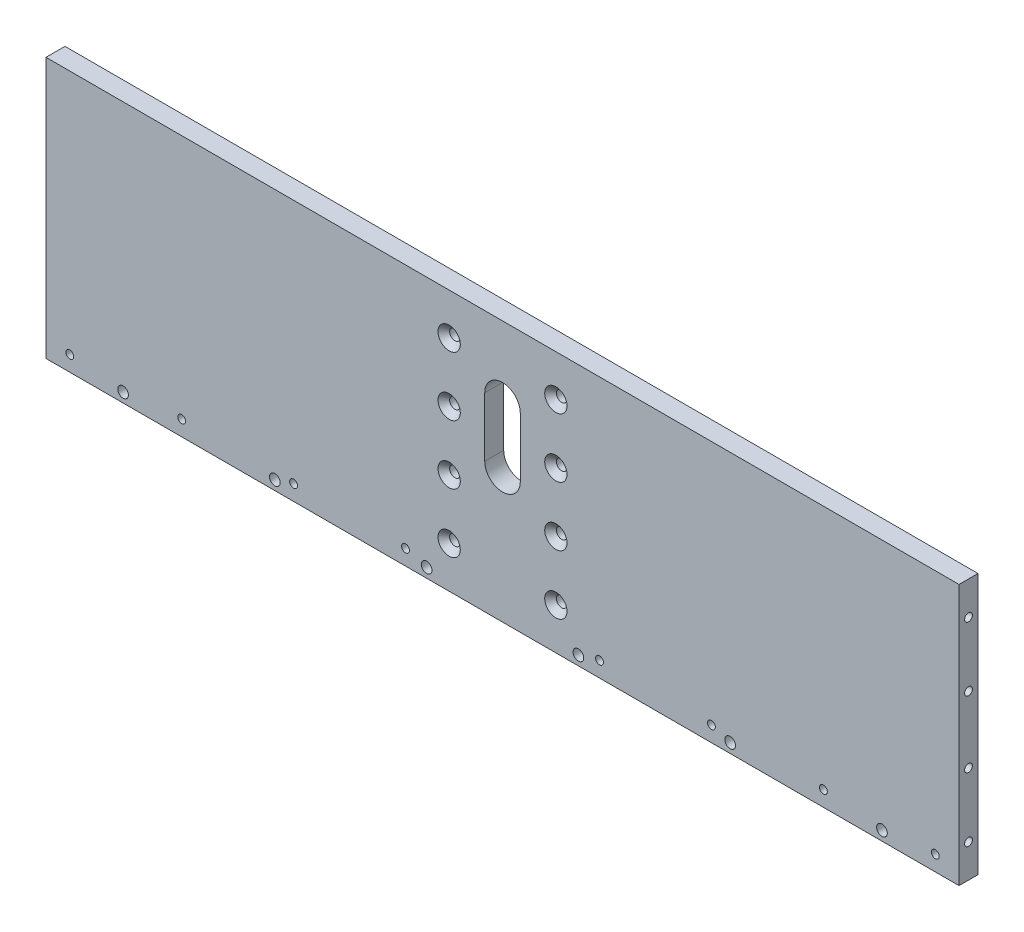
SolidWorks part; units mm, degrees
material "7079 Alloy"
ref_plane "Front Plane" through (0, 0, 0) normal (0, 0, 1) x (1, 0, 0)
ref_plane "Top Plane" through (0, 0, 0) normal (0, 1, 0) x (1, 0, 0)
ref_plane "Right Plane" through (0, 0, 0) normal (1, 0, 0) x (0, 0, -1)
sketch "Sketch1" plane through (0, 0, 0) normal (0, 0, 1) x (1, 0, 0)
  line L0 (-192.5, 0) -> (0, 0) construction
  line L1 (-192.5, -55) -> (192.5, -55)
  line L2 (-192.5, -55) -> (-192.5, 55)
  line L3 (-192.5, 55) -> (192.5, 55)
  line L4 (192.5, -55) -> (192.5, 55)
  line L5 (0, 0) -> (0, 55) construction
  dimension "D1" = 110
  dimension "D2" = 385
extrude "Extrude1" add sketch "Sketch1" along normal blind 8
sketch "Sketch2" plane through (0, 0, 8) normal (0, 0, 1) x (1, 0, 0)
  line L0 (0, 0) -> (0, 55) construction
  line L1 (192.5, 55) -> (-192.5, 55) construction
  line L2 (22.5, 55) -> (22.5, 49.9279) construction
  line L3 (22.5, 49.9279) -> (22.5, -49.9279) construction
  line L4 (22.5, -49.9279) -> (22.5, -55) construction
  line L5 (-192.5, -55) -> (192.5, -55) construction
  line L6 (192.5, -55) -> (192.5, 55) construction
  line L7 (22.5, 0) -> (192.5, 0) construction
  circle A0 centre (22.5, 37.5) radius 2
  circle A1 centre (22.5, 12.5) radius 2
  circle A2 centre (22.5, -12.5) radius 2
  circle A3 centre (-22.5, -12.5) radius 2
  circle A4 centre (-22.5, -37.5) radius 2
  circle A5 centre (22.5, -37.5) radius 2
  circle A6 centre (-22.5, 12.5) radius 2
  circle A7 centre (-22.5, 37.5) radius 2
  dimension "D6" = 4
  dimension "D1" = 37.5
  dimension "D2" = 45
  dimension "D5" = 25
extrude "Cut-Extrude1" cut sketch "Sketch2" against normal blind 10
hole_wizard "CSK for M4 Flat Head Machine Screw1" positions "Sketch4" profile "Sketch3" countersink size "M4" standard "Ansi Metric" end condition through all
sketch "Sketch4" plane through (0, 0, 8) normal (0, 0, 1) x (1, 0, 0)
  point P1 (22.5, 37.5)
  point P4 (22.5, 12.5)
  point P19 (-22.5, 12.5)
  point P25 (-22.5, 37.5)
  point P28 (22.5, -12.5)
  point P31 (-22.5, -12.5)
  point P34 (-22.5, -37.5)
  point P37 (22.5, -37.5)
sketch "Sketch3" plane through (22.5, 37.5, 8) normal (1, 0, 0) x (0, -1, 0)
  line L0 (0, 0) -> (0, 8)
  line L1 (0, 8) -> (2.25, 8)
  line L2 (2.25, 8) -> (2.25, 2.45)
  line L3 (2.25, 2.45) -> (4.7, 0)
  line L5 (4.7, 0) -> (0, 0)
  line L6 (-2.25, 2.45) -> (-4.7, 0) construction
  line L11 (0, -6.35) -> (0, 107.95) construction
  dimension "Thru Hole Dia." = 4.5
  dimension "Thru Hole Depth" = 8
  dimension "Near C'Sink Dia." = 9.4
  dimension "Near C'Sink Angle" = 90
sketch "Sketch5" plane through (192.5, 0, 0) normal (1, 0, 0) x (0, 0, -1)
  line L0 (-4, 55) -> (-4, -55) construction
  line L1 (-8, 55) -> (0, 55) construction
  line L2 (-8, -55) -> (0, -55) construction
  line L3 (0, 0) -> (-8, 0) construction
  line L4 (0, -55) -> (0, 55) construction
  line L5 (-8, -55) -> (-8, 55) construction
  circle A0 centre (-4, 41) radius 1.65
  circle A1 centre (-4, 14) radius 1.65
  circle A2 centre (-4, -41) radius 1.65
  circle A3 centre (-4, -14) radius 1.65
  dimension "D1" = 3.3
  dimension "D3" = 27
  dimension "D2" = 14
extrude "Cut-Extrude2" cut sketch "Sketch5" against normal blind 15
mirror "Mirror1" about plane through (0, 0, 0) normal (1, 0, 0) of "Cut-Extrude2"
sketch "Sketch6" plane through (0, 0, 0) normal (0, 0, -1) x (-1, 0, 0)
  line L0 (192.5, -55) -> (-192.5, -55) construction
  line L2 (0, -51) -> (-192.5, -51) construction
  line L3 (-192.5, -55) -> (-192.5, 55) construction
  circle A0 centre (-96, -51) radius 2.25
  circle A1 centre (-32, -51) radius 2.25
  circle A2 centre (32, -51) radius 2.25
  circle A3 centre (96, -51) radius 2.25
  circle A4 centre (-160, -51) radius 2.25
  circle A5 centre (160, -51) radius 2.25
  dimension "D2" = 6
  dimension "D4" = 4
  dimension "D5" = 4.5
  dimension "D3" = 64
  dimension "D1" = 32.5
extrude "Cut-Extrude3" cut sketch "Sketch6" against normal blind 10
sketch "Sketch9" plane through (0, 0, 0) normal (0, 0, -1) x (-1, 0, 0)
  line L0 (-167.5, 40) -> (-167.5, -40) construction
  line L1 (-162.5, 40) -> (-162.5, -40)
  line L2 (-172.5, 40) -> (-172.5, -40)
  line L3 (-192.5, -55) -> (-192.5, 55) construction
  line L4 (-192.5, 55) -> (192.5, 55) construction
  line L5 (-154.5, 40) -> (-154.5, -40) construction
  line L6 (-149.5, 40) -> (-149.5, -40)
  line L7 (-159.5, 40) -> (-159.5, -40)
  line L8 (-141.5, 40) -> (-141.5, -40) construction
  line L9 (-136.5, 40) -> (-136.5, -40)
  line L10 (-146.5, 40) -> (-146.5, -40)
  line L11 (-128.5, 40) -> (-128.5, -40) construction
  line L12 (-123.5, 40) -> (-123.5, -40)
  line L13 (-133.5, 40) -> (-133.5, -40)
  line L14 (-115.5, 40) -> (-115.5, -40) construction
  line L15 (-110.5, 40) -> (-110.5, -40)
  line L16 (-120.5, 40) -> (-120.5, -40)
  line L17 (-102.5, 40) -> (-102.5, -40) construction
  line L18 (-97.5, 40) -> (-97.5, -40)
  line L19 (-107.5, 40) -> (-107.5, -40)
  line L20 (-89.5, 40) -> (-89.5, -40) construction
  line L21 (-84.5, 40) -> (-84.5, -40)
  line L22 (-94.5, 40) -> (-94.5, -40)
  line L23 (-76.5, 40) -> (-76.5, -40) construction
  line L24 (-71.5, 40) -> (-71.5, -40)
  line L25 (-81.5, 40) -> (-81.5, -40)
  line L26 (-63.5, 40) -> (-63.5, -40) construction
  line L27 (-58.5, 40) -> (-58.5, -40)
  line L28 (-68.5, 40) -> (-68.5, -40)
  line L29 (-50.5, 40) -> (-50.5, -40) construction
  line L30 (-45.5, 40) -> (-45.5, -40)
  line L31 (-55.5, 40) -> (-55.5, -40)
  line L32 (-37.5, 40) -> (-37.5, -40) construction
  line L33 (-32.5, 40) -> (-32.5, -40)
  line L34 (-42.5, 40) -> (-42.5, -40)
  line L35 (0, 55) -> (0, -55) construction
  line L36 (192.5, -55) -> (-192.5, -55) construction
  line L37 (167.5, 40) -> (167.5, -40) construction
  line L38 (162.5, 40) -> (162.5, -40)
  line L39 (172.5, 40) -> (172.5, -40)
  line L40 (154.5, 40) -> (154.5, -40) construction
  line L41 (149.5, 40) -> (149.5, -40)
  line L42 (159.5, 40) -> (159.5, -40)
  line L43 (141.5, 40) -> (141.5, -40) construction
  line L44 (136.5, 40) -> (136.5, -40)
  line L45 (146.5, 40) -> (146.5, -40)
  line L46 (128.5, 40) -> (128.5, -40) construction
  line L47 (123.5, 40) -> (123.5, -40)
  line L48 (133.5, 40) -> (133.5, -40)
  line L49 (115.5, 40) -> (115.5, -40) construction
  line L50 (110.5, 40) -> (110.5, -40)
  line L51 (120.5, 40) -> (120.5, -40)
  line L52 (102.5, 40) -> (102.5, -40) construction
  line L53 (97.5, 40) -> (97.5, -40)
  line L54 (107.5, 40) -> (107.5, -40)
  line L55 (89.5, 40) -> (89.5, -40) construction
  line L56 (84.5, 40) -> (84.5, -40)
  line L57 (94.5, 40) -> (94.5, -40)
  line L58 (76.5, 40) -> (76.5, -40) construction
  line L59 (71.5, 40) -> (71.5, -40)
  line L60 (81.5, 40) -> (81.5, -40)
  line L61 (63.5, 40) -> (63.5, -40) construction
  line L62 (58.5, 40) -> (58.5, -40)
  line L63 (68.5, 40) -> (68.5, -40)
  line L64 (50.5, 40) -> (50.5, -40) construction
  line L65 (45.5, 40) -> (45.5, -40)
  line L66 (55.5, 40) -> (55.5, -40)
  line L67 (37.5, 40) -> (37.5, -40) construction
  line L68 (32.5, 40) -> (32.5, -40)
  line L69 (42.5, 40) -> (42.5, -40)
  arc A0 (-162.5, 40) -> (-172.5, 40) centre (-167.5, 40) ccw
  arc A1 (-172.5, -40) -> (-162.5, -40) centre (-167.5, -40) ccw
  arc A2 (-149.5, 40) -> (-159.5, 40) centre (-154.5, 40) ccw
  arc A3 (-159.5, -40) -> (-149.5, -40) centre (-154.5, -40) ccw
  arc A4 (-136.5, 40) -> (-146.5, 40) centre (-141.5, 40) ccw
  arc A5 (-146.5, -40) -> (-136.5, -40) centre (-141.5, -40) ccw
  arc A6 (-123.5, 40) -> (-133.5, 40) centre (-128.5, 40) ccw
  arc A7 (-133.5, -40) -> (-123.5, -40) centre (-128.5, -40) ccw
  arc A8 (-110.5, 40) -> (-120.5, 40) centre (-115.5, 40) ccw
  arc A9 (-120.5, -40) -> (-110.5, -40) centre (-115.5, -40) ccw
  arc A10 (-97.5, 40) -> (-107.5, 40) centre (-102.5, 40) ccw
  arc A11 (-107.5, -40) -> (-97.5, -40) centre (-102.5, -40) ccw
  arc A12 (-84.5, 40) -> (-94.5, 40) centre (-89.5, 40) ccw
  arc A13 (-94.5, -40) -> (-84.5, -40) centre (-89.5, -40) ccw
  arc A14 (-71.5, 40) -> (-81.5, 40) centre (-76.5, 40) ccw
  arc A15 (-81.5, -40) -> (-71.5, -40) centre (-76.5, -40) ccw
  arc A16 (-58.5, 40) -> (-68.5, 40) centre (-63.5, 40) ccw
  arc A17 (-68.5, -40) -> (-58.5, -40) centre (-63.5, -40) ccw
  arc A18 (-45.5, 40) -> (-55.5, 40) centre (-50.5, 40) ccw
  arc A19 (-55.5, -40) -> (-45.5, -40) centre (-50.5, -40) ccw
  arc A20 (-32.5, 40) -> (-42.5, 40) centre (-37.5, 40) ccw
  arc A21 (-42.5, -40) -> (-32.5, -40) centre (-37.5, -40) ccw
  arc A22 (162.5, 40) -> (172.5, 40) centre (167.5, 40) cw
  arc A23 (172.5, -40) -> (162.5, -40) centre (167.5, -40) cw
  arc A24 (149.5, 40) -> (159.5, 40) centre (154.5, 40) cw
  arc A25 (159.5, -40) -> (149.5, -40) centre (154.5, -40) cw
  arc A26 (136.5, 40) -> (146.5, 40) centre (141.5, 40) cw
  arc A27 (146.5, -40) -> (136.5, -40) centre (141.5, -40) cw
  arc A28 (123.5, 40) -> (133.5, 40) centre (128.5, 40) cw
  arc A29 (133.5, -40) -> (123.5, -40) centre (128.5, -40) cw
  arc A30 (110.5, 40) -> (120.5, 40) centre (115.5, 40) cw
  arc A31 (120.5, -40) -> (110.5, -40) centre (115.5, -40) cw
  arc A32 (97.5, 40) -> (107.5, 40) centre (102.5, 40) cw
  arc A33 (107.5, -40) -> (97.5, -40) centre (102.5, -40) cw
  arc A34 (84.5, 40) -> (94.5, 40) centre (89.5, 40) cw
  arc A35 (94.5, -40) -> (84.5, -40) centre (89.5, -40) cw
  arc A36 (71.5, 40) -> (81.5, 40) centre (76.5, 40) cw
  arc A37 (81.5, -40) -> (71.5, -40) centre (76.5, -40) cw
  arc A38 (58.5, 40) -> (68.5, 40) centre (63.5, 40) cw
  arc A39 (68.5, -40) -> (58.5, -40) centre (63.5, -40) cw
  arc A40 (45.5, 40) -> (55.5, 40) centre (50.5, 40) cw
  arc A41 (55.5, -40) -> (45.5, -40) centre (50.5, -40) cw
  arc A42 (32.5, 40) -> (42.5, 40) centre (37.5, 40) cw
  arc A43 (42.5, -40) -> (32.5, -40) centre (37.5, -40) cw
  point P2 (-167.5, 0)
  point P14 (-154.5, 0)
  point P21 (-141.5, 0)
  point P28 (-128.5, 0)
  point P35 (-115.5, 0)
  point P42 (-102.5, 0)
  point P49 (-89.5, 0)
  point P56 (-76.5, 0)
  point P63 (-63.5, 0)
  point P70 (-50.5, 0)
  point P77 (-37.5, 0)
  point P87 (167.5, 0)
  point P94 (154.5, 0)
  point P101 (141.5, 0)
  point P108 (128.5, 0)
  point P115 (115.5, 0)
  point P122 (102.5, 0)
  point P129 (89.5, 0)
  point P136 (76.5, 0)
  point P143 (63.5, 0)
  point P150 (50.5, 0)
  point P157 (37.5, 0)
  dimension "D1" = 25
  dimension "D2" = 10
  dimension "D3" = 55
  dimension "D4" = 80
  dimension "D6" = 13
  dimension "D5" = 11
extrude "Cut-Extrude4" cut sketch "Sketch9" against normal blind 6
sketch "Sketch10" plane through (0, 0, 8) normal (0, 0, 1) x (1, 0, 0)
  line L0 (0, 0) -> (0, 25) construction
  line L1 (-7.5, 0) -> (-7.5, 25)
  line L2 (7.5, 0) -> (7.5, 25)
  arc A0 (-7.5, 0) -> (7.5, 0) centre (0, 0) ccw
  arc A1 (7.5, 25) -> (-7.5, 25) centre (0, 25) ccw
  point P2 (0, 12.5)
  dimension "D1" = 7.5
  dimension "D2" = 25
extrude "Cut-Extrude5" cut sketch "Sketch10" against normal blind 10
hole_wizard "CSK for M4 Flat Head Machine Screw2" positions "Sketch12" profile "Sketch11" countersink size "M4" standard "Ansi Metric" end condition through all
sketch "Sketch12" plane through (0, 0, 0) normal (0, 0, -1) x (-1, 0, 0)
  point P1 (-160, -51)
  point P4 (-96, -51)
  point P7 (-32, -51)
  point P10 (32, -51)
  point P13 (96, -51)
  point P16 (160, -51)
sketch "Sketch11" plane through (160, -51, 0) normal (1, 0, 0) x (0, 1, 0)
  line L0 (0, 0) -> (0, 8)
  line L1 (0, 8) -> (2.25, 8)
  line L2 (2.25, 8) -> (2.25, 2.45)
  line L3 (2.25, 2.45) -> (4.7, 0)
  line L5 (4.7, 0) -> (0, 0)
  line L6 (-2.25, 2.45) -> (-4.7, 0) construction
  line L11 (0, -6.35) -> (0, 107.95) construction
  dimension "Thru Hole Dia." = 4.5
  dimension "Thru Hole Depth" = 8
  dimension "Near C'Sink Dia." = 9.4
  dimension "Near C'Sink Angle" = 90
sketch "Sketch13" plane through (0, 0, 0) normal (0, 0, -1) x (-1, 0, 0)
  line L0 (0, -55) -> (0, -48.5) construction
  line L1 (29.5322, -55) -> (-29.5322, -55) construction
  line L2 (0, -48.5) -> (-192.5, -48.5) construction
  line L3 (-192.5, -55) -> (-192.5, 55) construction
  circle A0 centre (-182.5, -48.5) radius 1.65
  circle A1 centre (-135.3, -48.5) radius 1.65
  circle A2 centre (-88.1, -48.5) radius 1.65
  circle A3 centre (-40.9, -48.5) radius 1.65
  circle A4 centre (40.9, -48.5) radius 1.65
  circle A5 centre (88.1, -48.5) radius 1.65
  circle A6 centre (135.3, -48.5) radius 1.65
  circle A7 centre (182.5, -48.5) radius 1.65
  dimension "D4" = 47.2
  dimension "D5" = 3.3
  dimension "D1" = 10
  dimension "D2" = 6.5
  dimension "D3" = 4
extrude "Cut-Extrude6" cut sketch "Sketch13" against normal blind 10
